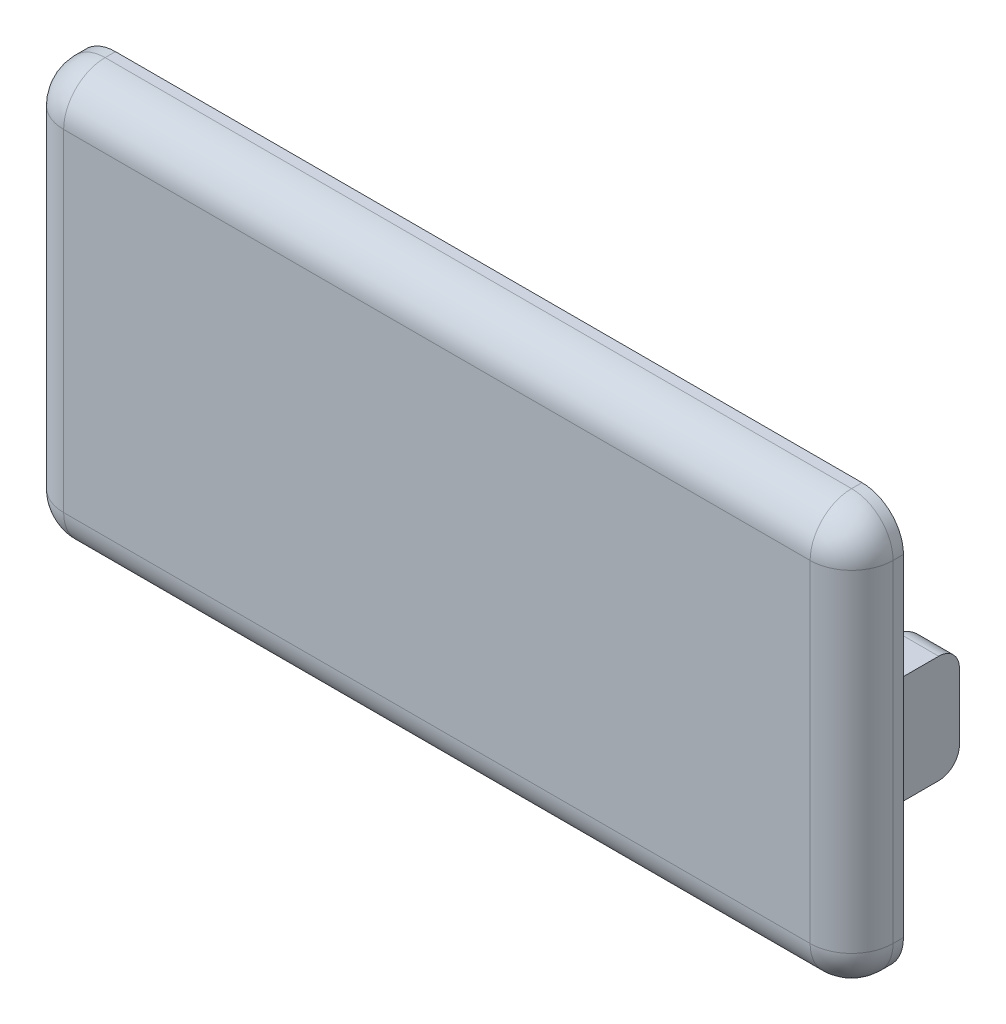
SolidWorks part; units mm, degrees
ref_plane "Front Plane" through (0, 0, 0) normal (0, 0, 1) x (1, 0, 0)
ref_plane "Top Plane" through (0, 0, 0) normal (0, 1, 0) x (1, 0, 0)
ref_plane "Right Plane" through (0, 0, 0) normal (1, 0, 0) x (0, 0, -1)
sketch "Sketch1" plane through (0, 0, 0) normal (0, 0, 1) x (1, 0, 0)
  line L0 (-20, 0) -> (20, 0) construction
  line L1 (-20, 10) -> (20, 10)
  line L2 (-20, 10) -> (-20, -10)
  line L3 (-20, -10) -> (20, -10)
  line L4 (20, 10) -> (20, -10)
  line L5 (0, 10) -> (0, -10) construction
  dimension "D1" = 20
  dimension "D2" = 40
extrude "Boss-Extrude1" add sketch "Sketch1" along normal blind 2.5
fillet "Fillet1" radius 2 8 edges at (0, 10, 2.5) (20, 0, 2.5) (0, -10, 2.5) (-20, 0, 2.5) (-20, -10, 1.25) (20, -10, 1.25) (20, 10, 1.25) (-20, 10, 1.25)
sketch "Sketch2" plane through (0, 0, 0) normal (0, 0, -1) x (-1, 0, 0)
  line L1 (17, -7) -> (-17, -7)
  line L2 (17, -7) -> (17, 7)
  line L3 (17, 7) -> (-17, 7)
  line L4 (-17, -7) -> (-17, 7)
  line L5 (17, -7) -> (-17, 7) construction
  line L6 (17, 7) -> (-17, -7) construction
  point P0 (0, 0)
  dimension "D1" = 34
  dimension "D2" = 14
extrude "Cut-Extrude1" cut sketch "Sketch2" against normal blind 1
sketch "Sketch3" plane through (0, 0, 0) normal (0, 1, 0) x (0, 0, -1)
  line L0 (0, -17) -> (3, -18.0919)
  line L2 (3, -18.0919) -> (3, -19.7)
  line L3 (3, -19.7) -> (0, -19.7)
  line L4 (0, -19.7) -> (0, -17)
  dimension "D1" = 2.7
  dimension "D2" = 3
  dimension "D3" = 110
extrude "Boss-Extrude2" add sketch "Sketch3" along normal mid plane 5.2
fillet "Fillet2" radius 1 2 edges at (18.896, -2.6, -3) (18.896, 2.6, -3)
sketch "Sketch4" plane through (0, 0, 1) normal (0, 0, -1) x (-1, 0, 0)
  line L0 (-10, 2.25) -> (-10, -2.25) construction
  line L1 (-12.25, 0) -> (-7.75, 0) construction
  line L2 (-12.0156, -1) -> (-11, -1)
  line L3 (-11, 2.0156) -> (-11, 1)
  line L4 (-12.0156, 1) -> (-11, 1)
  line L5 (-9, 2.0156) -> (-9, 1)
  line L6 (-11, -1) -> (-11, -2.0156)
  line L7 (-9, -1) -> (-7.9844, -1)
  line L8 (-11, 2.25) -> (-11, -2.25) construction
  line L9 (-9, 1) -> (-7.9844, 1)
  line L10 (-2.3, -1) -> (2.3, -1) construction
  line L11 (-9, -1) -> (-9, -2.0156)
  line L12 (-2.3, 1) -> (2.3, 1) construction
  line L13 (-2.3, 0) -> (2.3, 0) construction
  line L14 (-9, 2.25) -> (-9, -2.25) construction
  line L15 (-10, 0) -> (10, 0) construction
  arc A0 (-12.0156, 1) -> (-12.0156, -1) centre (-10, 0) ccw
  arc A1 (-9, 2.0156) -> (-11, 2.0156) centre (-10, 0) ccw
  arc A2 (-7.9844, -1) -> (-7.9844, 1) centre (-10, 0) ccw
  arc A3 (-11, -2.0156) -> (-9, -2.0156) centre (-10, 0) ccw
  dimension "D1" = 4.5
  dimension "D4" = 20
  dimension "D2" = 1
  dimension "D3" = 1
extrude "Boss-Extrude3" add sketch "Sketch4" along normal blind 7
sketch "Sketch5" plane through (0, 0, 0) normal (0, 1, 0) x (0, 0, -1)
  line L0 (-1, -10) -> (6, -10) construction
  line L1 (6, -11) -> (6, -9) construction
  line L2 (4, -7.75) -> (6, -7.75)
  line L3 (6, -7.75) -> (6, -8.5222)
  line L6 (4, -7.75) -> (5.5868, -8.0298)
  arc A0 (5.5868, -8.0298) -> (6, -8.5222) centre (5.5, -8.5222) cw
  dimension "D1" = 2
  dimension "D2" = 0.5
  dimension "D3" = 10
revolve "Cut-Revolve1" cut sketch "Sketch5" angle 360 about L0
sketch "Sketch6" plane through (0, 0, 1) normal (0, 0, -1) x (-1, 0, 0)
  line L0 (-13.5, 0) -> (-6.5, 0) construction
  line L1 (-13.3541, -1) -> (-6.6459, -1)
  line L2 (-13.3541, 1) -> (-6.6459, 1)
  line L3 (-13.5856, 0) -> (-6.5, 0) construction
  line L4 (-13.5856, 1) -> (-6.5, 1) construction
  line L5 (-13.5856, -1) -> (-6.5, -1) construction
  arc A0 (-6.6459, -1) -> (-6.6459, 1) centre (-10, 0) ccw
  arc A1 (-13.3541, 1) -> (-13.3541, -1) centre (-10, 0) ccw
  dimension "D1" = 7
  dimension "D2" = 1
  dimension "D3" = 1
extrude "Boss-Extrude4" add sketch "Sketch6" along normal blind 0.6
pattern_linear "LPattern1" count 2 spacing 20 along (-1, 0, 0) of "Boss-Extrude3", "Cut-Revolve1", "Boss-Extrude4"
